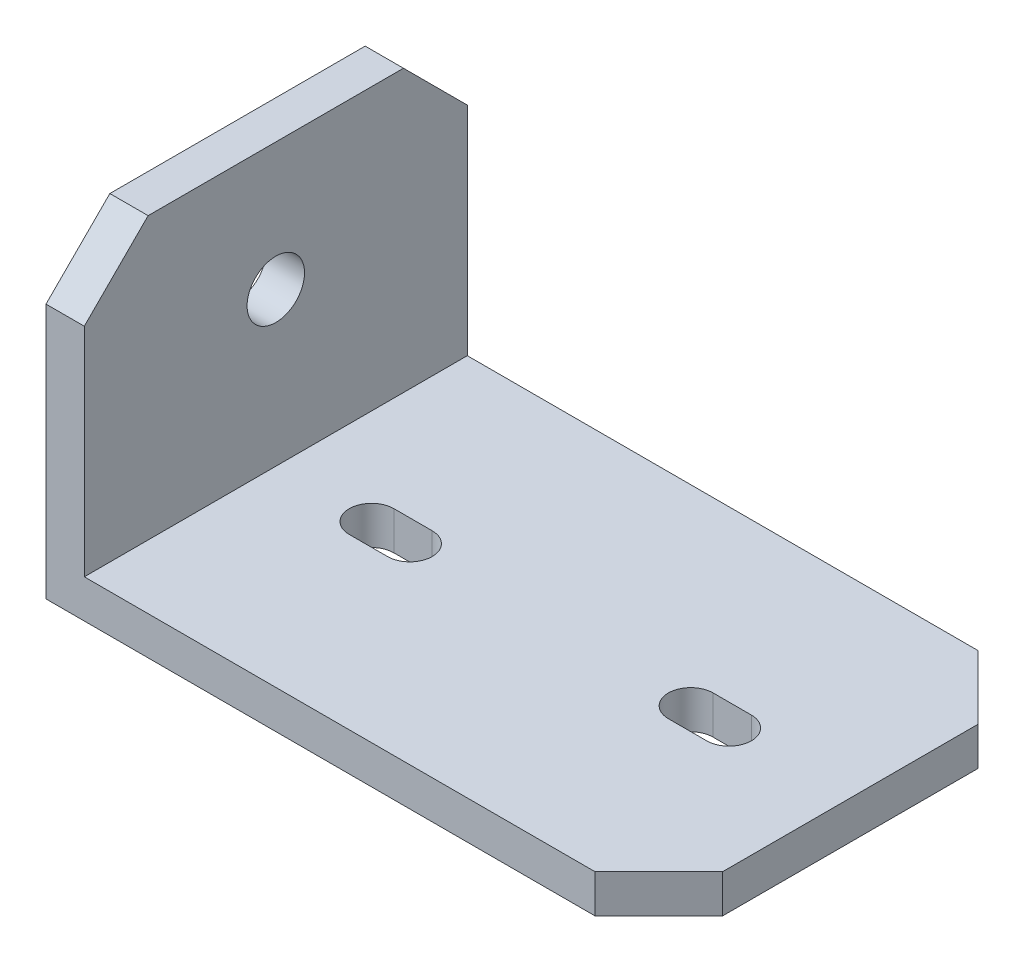
SolidWorks part; units mm, degrees
ref_plane "Front Plane" through (0, 0, 0) normal (0, 0, 1) x (1, 0, 0)
ref_plane "Top Plane" through (0, 0, 0) normal (0, 1, 0) x (1, 0, 0)
ref_plane "Right Plane" through (0, 0, 0) normal (1, 0, 0) x (0, 0, -1)
sketch "Sketch1" plane through (0, 0, 0) normal (0, 0, 1) x (1, 0, 0)
  line L0 (0, 22) -> (0, 0)
  line L1 (0, 0) -> (45, 0)
  line L2 (45, 0) -> (45, -3)
  line L3 (45, -3) -> (-3, -3)
  line L4 (-3, -3) -> (-3, 22)
  line L5 (-3, 22) -> (0, 22)
  dimension "D1" = 3
  dimension "D2" = 3
  dimension "D3" = 48
  dimension "D4" = 25
extrude "Boss-Extrude1" add sketch "Sketch1" along normal blind 30
sketch "Sketch2" plane through (0, 0, 0) normal (1, 0, 0) x (0, 0, -1)
  line L0 (-15, 0) -> (-15, 22) construction
  line L1 (-30, 0) -> (0, 0) construction
  line L2 (-30, 22) -> (0, 22) construction
  circle A0 centre (-15, 12) radius 2.25
  dimension "D2" = 4.5
  dimension "D1" = 12
extrude "Cut-Extrude1" cut sketch "Sketch2" against normal blind 30
sketch "Sketch3" plane through (0, 0, 0) normal (0, 1, 0) x (1, 0, 0)
  line L0 (0, -15) -> (9, -15) construction
  line L1 (0, -30) -> (0, 0) construction
  line L2 (9, -15) -> (34, -15) construction
  line L3 (34, -15) -> (45, -15) construction
  line L4 (45, -30) -> (45, 0) construction
  line L5 (7.5, -15) -> (10.5, -15) construction
  line L6 (7.5, -13.25) -> (10.5, -13.25)
  line L7 (7.5, -16.75) -> (10.5, -16.75)
  line L8 (32.5, -15) -> (35.5, -15) construction
  line L9 (32.5, -13.25) -> (35.5, -13.25)
  line L10 (32.5, -16.75) -> (35.5, -16.75)
  arc A0 (7.5, -13.25) -> (7.5, -16.75) centre (7.5, -15) ccw
  arc A1 (10.5, -16.75) -> (10.5, -13.25) centre (10.5, -15) ccw
  arc A2 (32.5, -13.25) -> (32.5, -16.75) centre (32.5, -15) ccw
  arc A3 (35.5, -16.75) -> (35.5, -13.25) centre (35.5, -15) ccw
  point P10 (9, -15)
  point P16 (34, -15)
  dimension "D1" = 1.75
  dimension "D2" = 25
  dimension "D4" = 3
  dimension "D3" = 11
extrude "Cut-Extrude2" cut sketch "Sketch3" against normal blind 30
chamfer "Chamfer1" distance 5 angle 45 4 edges at (-1.5, 22, 30) (-1.5, 22, 0) (45, -1.5, 30) (45, -1.5, 0)
